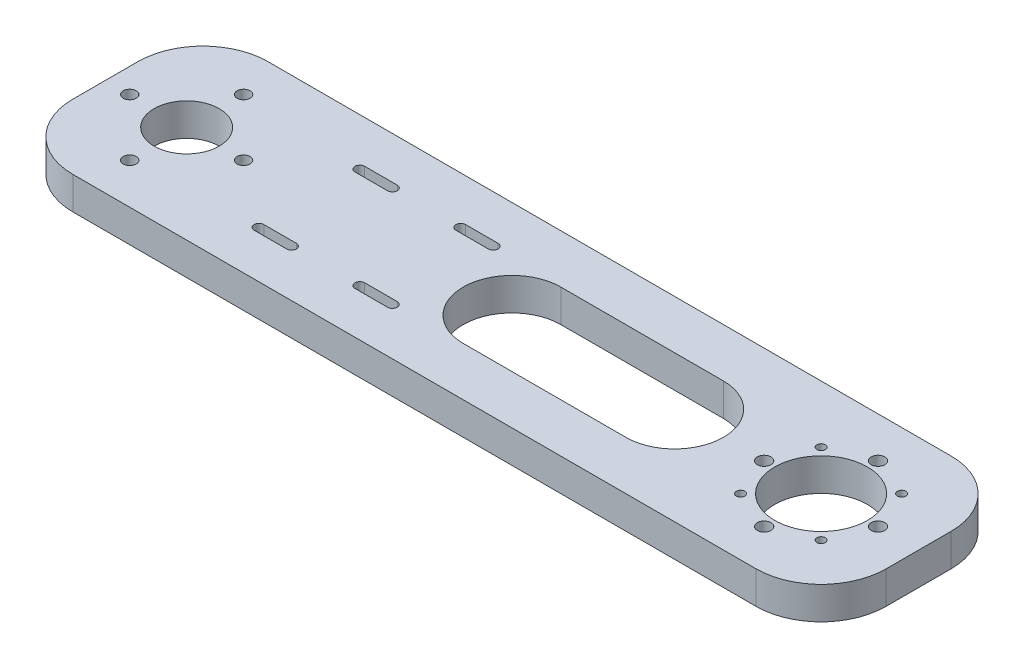
SolidWorks part; units mm, degrees
ref_plane "前视基准面" through (0, 0, 0) normal (0, 0, 1) x (1, 0, 0)
ref_plane "上视基准面" through (0, 0, 0) normal (0, 1, 0) x (1, 0, 0)
ref_plane "右视基准面" through (0, 0, 0) normal (1, 0, 0) x (0, 0, -1)
other "Configuration Table"
sketch "草图1" plane through (0, 0, 0) normal (0, 1, 0) x (1, 0, 0)
  line L1 (-125, -30) -> (125, -30)
  line L2 (-125, -30) -> (-125, 30)
  line L3 (-125, 30) -> (125, 30)
  line L4 (125, -30) -> (125, 30)
  line L5 (-125, -30) -> (125, 30) construction
  line L6 (-125, 30) -> (125, -30) construction
  point P0 (0, 0)
  dimension "D1" = 250
  dimension "D2" = 60
extrude "凸台-拉伸1" add sketch "草图1" along normal blind 10
fillet "圆角1" radius 20 4 edges at (-125, 5, -30) (-125, 5, 30) (125, 5, -30) (125, 5, 30)
sketch "草图5" plane through (0, 0, 0) normal (0, -1, 0) x (1, 0, 0)
  line L1 (-105, 30) -> (105, 30) construction
  line L2 (-125, -10) -> (-125, 10) construction
  circle A0 centre (-100, 0) radius 10
  dimension "D1" = 20
  dimension "D2" = 30
  dimension "D3" = 25
extrude "切除-拉伸3" cut sketch "草图5" against normal blind 10
sketch "草图15" plane through (0, 0, 0) normal (0, -1, 0) x (1, 0, 0)
  line L0 (125, 10) -> (125, -10) construction
  line L1 (-105, 30) -> (105, 30) construction
  circle A0 centre (95, 0) radius 14.25
  dimension "D1" = 30
  dimension "D2" = 30
  dimension "D3" = 28.5
extrude "切除-拉伸12" cut sketch "草图15" against normal through all
sketch "草图18" plane through (0, 0, 0) normal (0, -1, 0) x (1, 0, 0)
  circle A0 centre (82.6256, 12.3744) radius 1.3
  circle A1 centre (107.3744, 12.3744) radius 1.3
  circle A2 centre (107.3744, -12.3744) radius 1.3
  circle A3 centre (82.6256, -12.3744) radius 1.3
  dimension "D1" = 2.6
  dimension "D2" = 2.6
  dimension "D3" = 2.6
  dimension "D4" = 2.6
extrude "切除-拉伸14" cut sketch "草图18" against normal through all
cosmetic thread "装饰螺纹线5" parameters "D2"=3.6
cosmetic thread "装饰螺纹线6" parameters "D2"=3.6
cosmetic thread "装饰螺纹线7" parameters "D2"=3.6
cosmetic thread "装饰螺纹线8" parameters "D2"=3.6
sketch "草图19" plane through (0, 0, 0) normal (0, -1, 0) x (-1, 0, 0)
  line L0 (62.2654, -15.5) -> (52.2654, -15.5) construction
  line L3 (125, 0) -> (-125, 0) construction
  line L4 (125, 10) -> (125, -10) construction
  line L5 (-125, -10) -> (-125, 10) construction
  line L6 (62.2654, 15.5) -> (52.2654, 15.5) construction
  line L7 (62.2654, 17) -> (52.2654, 17)
  line L8 (62.2654, 14) -> (52.2654, 14)
  line L9 (31.2654, -15.5) -> (21.2654, -15.5) construction
  line L10 (31.2654, -17) -> (21.2654, -17)
  line L11 (31.2654, -14) -> (21.2654, -14)
  line L12 (31.2654, 15.5) -> (21.2654, 15.5) construction
  line L13 (31.2654, 17) -> (21.2654, 17)
  line L14 (31.2654, 14) -> (21.2654, 14)
  line L15 (62.2654, -17) -> (52.2654, -17)
  line L16 (62.2654, -14) -> (52.2654, -14)
  arc A2 (62.2654, 17) -> (62.2654, 14) centre (62.2654, 15.5) cw
  arc A3 (52.2654, 14) -> (52.2654, 17) centre (52.2654, 15.5) cw
  arc A4 (31.2654, -17) -> (31.2654, -14) centre (31.2654, -15.5) ccw
  arc A5 (21.2654, -14) -> (21.2654, -17) centre (21.2654, -15.5) ccw
  arc A6 (31.2654, 17) -> (31.2654, 14) centre (31.2654, 15.5) cw
  arc A7 (21.2654, 14) -> (21.2654, 17) centre (21.2654, 15.5) cw
  arc A8 (62.2654, -17) -> (62.2654, -14) centre (62.2654, -15.5) ccw
  arc A9 (52.2654, -14) -> (52.2654, -17) centre (52.2654, -15.5) ccw
  point P2 (57.2654, -15.5)
  point P17 (57.2654, 15.5)
  point P24 (26.2654, -15.5)
  point P31 (26.2654, 15.5)
  dimension "D4" = 10
  dimension "D3" = 3
extrude "切除-拉伸15" cut sketch "草图19" against normal through all
sketch "草图20" plane through (0, 10, 0) normal (0, 1, 0) x (1, 0, 0)
  line L0 (-100, 10) -> (-100, -10) construction
  line L1 (-110, 0) -> (-90, 0) construction
  circle A4 centre (-100, 0) radius 10 construction
  circle A5 centre (-100, 0) radius 17.5 construction
  circle A6 centre (-100, 17.5) radius 2
  dimension "D1" = 4
extrude "切除-拉伸16" cut sketch "草图20" against normal blind 10
sketch "草图21" plane through (0, 0, 0) normal (0, -1, 0) x (1, 0, 0)
  circle A0 centre (95, 0) radius 17.5
  circle A1 centre (95, 17.5) radius 2.1
  circle A2 centre (112.5, 0) radius 2.1
  circle A3 centre (95, -17.5) radius 2.1
  circle A4 centre (77.5, 0) radius 2.1
  dimension "D1" = 35
  dimension "D2" = 4.2
  dimension "D3" = 4.2
  dimension "D4" = 4.2
  dimension "D5" = 4.2
extrude "切除-拉伸17" cut sketch "草图21" against normal blind 10 contours A0 A1 | A0 A1 | A0 A2 | A0 A2 | A0 A3 | A0 A4 | A0 A4
cosmetic thread "装饰螺纹线1" parameters "D2"=5.2
cosmetic thread "装饰螺纹线2" parameters "D2"=5.2
cosmetic thread "装饰螺纹线3" parameters "D2"=5.2
cosmetic thread "装饰螺纹线4" parameters "D2"=5.2
sketch "草图22" plane through (0, 10, 0) normal (0, 1, 0) x (1, 0, 0)
  line L0 (0, 0) -> (50, 0) construction
  line L1 (0, 15) -> (50, 15)
  line L2 (0, -15) -> (50, -15)
  line L3 (105, 30) -> (-105, 30) construction
  line L4 (125, -10) -> (125, 10) construction
  arc A0 (0, 15) -> (0, -15) centre (0, 0) ccw
  arc A1 (50, -15) -> (50, 15) centre (50, 0) ccw
  point P2 (25, 0)
  dimension "D3" = 100
  dimension "D1" = 50
  dimension "D2" = 15
extrude "切除-拉伸18" cut sketch "草图22" against normal through all
pattern_circular "阵列(圆周)1" count 4 every 90 about axis through (-100, 0, 0) along (0, 1, 0) of "切除-拉伸16"
